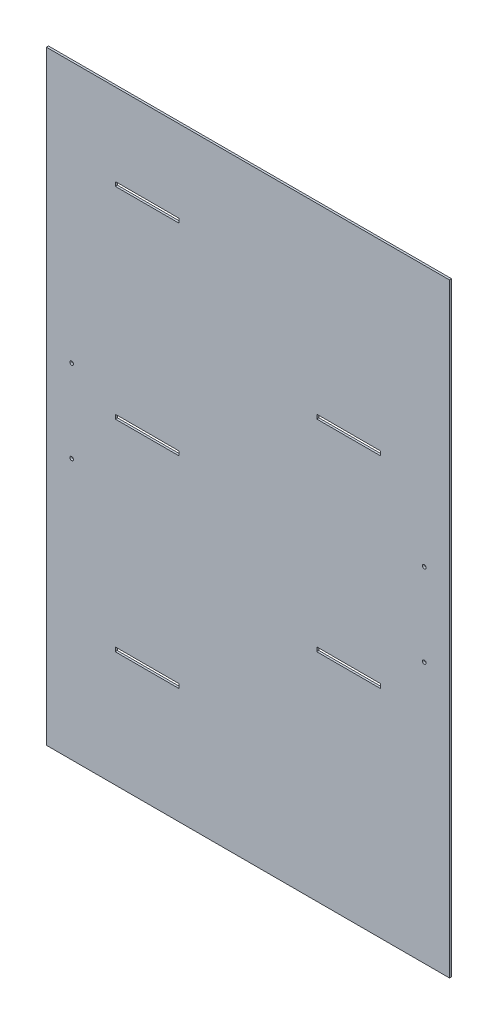
SolidWorks part; units mm, degrees
ref_plane "Front Plane" through (0, 0, 0) normal (0, 0, 1) x (1, 0, 0)
ref_plane "Top Plane" through (0, 0, 0) normal (0, 1, 0) x (1, 0, 0)
ref_plane "Right Plane" through (0, 0, 0) normal (1, 0, 0) x (0, 0, -1)
sketch "Sketch1" plane through (0, 0, 0) normal (0, 0, 1) x (1, 0, 0)
  line L1 (-304.8, -457.2) -> (304.8, -457.2)
  line L2 (-304.8, -457.2) -> (-304.8, 457.2)
  line L3 (-304.8, 457.2) -> (304.8, 457.2)
  line L4 (304.8, -457.2) -> (304.8, 457.2)
  line L5 (-304.8, -457.2) -> (304.8, 457.2) construction
  line L6 (-304.8, 457.2) -> (304.8, -457.2) construction
  point P0 (0, 0)
  dimension "D1" = 609.6
  dimension "D2" = 914.4
extrude "Boss-Extrude1" add sketch "Sketch1" along normal mid plane 3.175
sketch "Sketch2" plane through (0, 0, 1.5875) normal (0, 0, 1) x (1, 0, 0)
  line L0 (304.8, 457.2) -> (-304.8, 457.2) construction
  line L1 (-200.66, 327.025) -> (-104.14, 327.025)
  line L2 (-200.66, 327.025) -> (-200.66, 333.375)
  line L3 (-200.66, 333.375) -> (-104.14, 333.375)
  line L4 (-104.14, 327.025) -> (-104.14, 333.375)
  line L5 (-200.66, 327.025) -> (-104.14, 333.375) construction
  line L6 (-200.66, 333.375) -> (-104.14, 327.025) construction
  line L7 (104.14, 174.625) -> (200.66, 174.625)
  line L8 (104.14, 174.625) -> (104.14, 180.975)
  line L9 (104.14, 180.975) -> (200.66, 180.975)
  line L10 (200.66, 174.625) -> (200.66, 180.975)
  line L11 (104.14, 174.625) -> (200.66, 180.975) construction
  line L12 (104.14, 180.975) -> (200.66, 174.625) construction
  line L13 (-304.8, 457.2) -> (0, 457.2) construction
  line L14 (0, 457.2) -> (304.8, 457.2) construction
  line L15 (-152.4, 457.2) -> (-152.4, -457.2) construction
  line L16 (-304.8, -457.2) -> (304.8, -457.2) construction
  line L17 (152.4, 457.2) -> (152.4, -457.2) construction
  line L19 (-200.66, 22.225) -> (-104.14, 22.225)
  line L20 (-200.66, 22.225) -> (-200.66, 28.575)
  line L21 (-200.66, 28.575) -> (-104.14, 28.575)
  line L22 (-104.14, 22.225) -> (-104.14, 28.575)
  line L23 (-200.66, 22.225) -> (-104.14, 28.575) construction
  line L24 (-200.66, 28.575) -> (-104.14, 22.225) construction
  line L25 (104.14, -130.175) -> (200.66, -130.175)
  line L26 (104.14, -130.175) -> (104.14, -123.825)
  line L27 (104.14, -123.825) -> (200.66, -123.825)
  line L28 (200.66, -130.175) -> (200.66, -123.825)
  line L29 (104.14, -130.175) -> (200.66, -123.825) construction
  line L30 (104.14, -123.825) -> (200.66, -130.175) construction
  line L31 (-200.66, -282.575) -> (-104.14, -282.575)
  line L32 (-200.66, -282.575) -> (-200.66, -276.225)
  line L33 (-200.66, -276.225) -> (-104.14, -276.225)
  line L34 (-104.14, -282.575) -> (-104.14, -276.225)
  line L35 (-200.66, -282.575) -> (-104.14, -276.225) construction
  line L36 (-200.66, -276.225) -> (-104.14, -282.575) construction
  point P0 (-152.4, 330.2)
  point P5 (152.4, 177.8)
  point P23 (152.4, -127)
  point P25 (-152.4, 25.4)
  point P35 (-152.4, -279.4)
  dimension "D1" = 96.52
  dimension "D2" = 96.52
  dimension "D3" = 6.35
  dimension "D4" = 6.35
  dimension "D5" = 127
  dimension "D6" = 152.4
  dimension "D7" = 152.4
  dimension "D8" = 152.4
  dimension "D9" = 152.4
extrude "Cut-Extrude1" cut sketch "Sketch2" against normal through all contours L7 L10 L9 L8 | L19 L22 L21 L20 | L25 L28 L27 L26 | L31 L34 L33 L32 | L4 L3 L2 L1
sketch "Sketch3" plane through (0, 0, 1.5875) normal (0, 0, 1) x (1, 0, 0)
  point P0 (266.7, 62.5)
  point P1 (266.7, -62.5)
  point P3 (-266.7, 62.5)
  point P4 (-266.7, -62.5)
hole_wizard "M5 Clearance Hole1" positions "Sketch4" profile "Sketch6" hole size "M5" standard "ANSI Metric" end condition through all
sketch "Sketch4" plane through (0, 0, 1.5875) normal (0, 0, 1) x (1, 0, 0)
  point P0 (-266.7, 62.5)
  point P3 (-266.7, -62.5)
  point P6 (266.7, 62.5)
  point P9 (266.7, -62.5)
sketch "Sketch6" plane through (-266.7, 62.5, 1.5875) normal (1, 0, 0) x (0, -1, 0)
  line L0 (0, 0) -> (0, 3.175)
  line L1 (0, 3.175) -> (2.75, 3.175)
  line L2 (2.75, 3.175) -> (2.75, 0)
  line L5 (2.75, 0) -> (0, 0)
  line L11 (0, -6.35) -> (0, 107.95) construction
  dimension "Thru Hole Dia." = 5.5
  dimension "Thru Hole Depth" = 3.175
